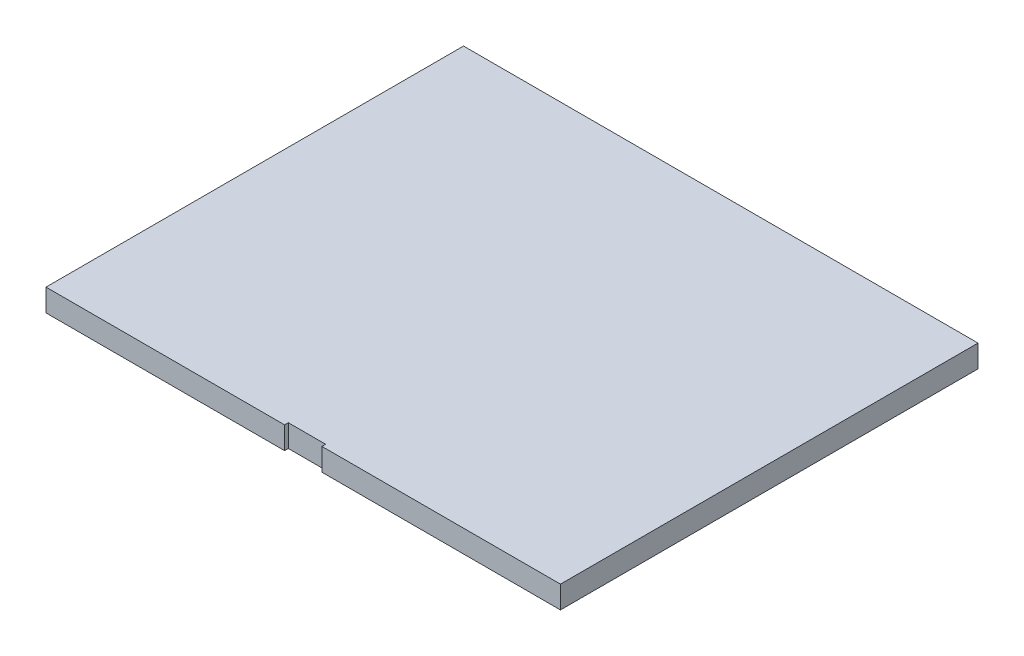
SolidWorks part; units mm, degrees
ref_plane "Front" through (0, 0, 0) normal (0, 0, 1) x (1, 0, 0)
ref_plane "Top" through (0, 0, 0) normal (0, 1, 0) x (1, 0, 0)
ref_plane "Right" through (0, 0, 0) normal (1, 0, 0) x (0, 0, -1)
sketch "Sketch1" plane through (0, 0, 0) normal (0, 1, 0) x (1, 0, 0)
  line L1 (0, 0) -> (438.15, 0)
  line L2 (0, 0) -> (0, 355.6)
  line L3 (0, 355.6) -> (438.15, 355.6)
  line L4 (438.15, 0) -> (438.15, 355.6)
  line L5 (0, 0) -> (438.15, 355.6) construction
  line L6 (0, 355.6) -> (438.15, 0) construction
  point P4 (219.075, 177.8)
  dimension "D1" = 355.6
  dimension "D2" = 438.15
extrude "Boss-Extrude1" add sketch "Sketch1" along normal blind 19.05
sketch "Sketch2" plane through (0, 19.05, 0) normal (0, 1, 0) x (1, 0, 0)
  line L0 (203.2, 0) -> (203.2, 3.175) construction
  line L1 (234.95, 3.175) -> (234.95, 0) construction
  line L2 (203.2, 3.175) -> (234.95, 3.175) construction
  line L3 (203.2, 0) -> (203.2, 3.175)
  line L4 (234.95, 3.175) -> (234.95, 0)
  line L5 (203.2, 3.175) -> (234.95, 3.175)
  line L6 (234.95, 0) -> (203.2, 0)
extrude "Cut-Extrude1" cut sketch "Sketch2" against normal through all
